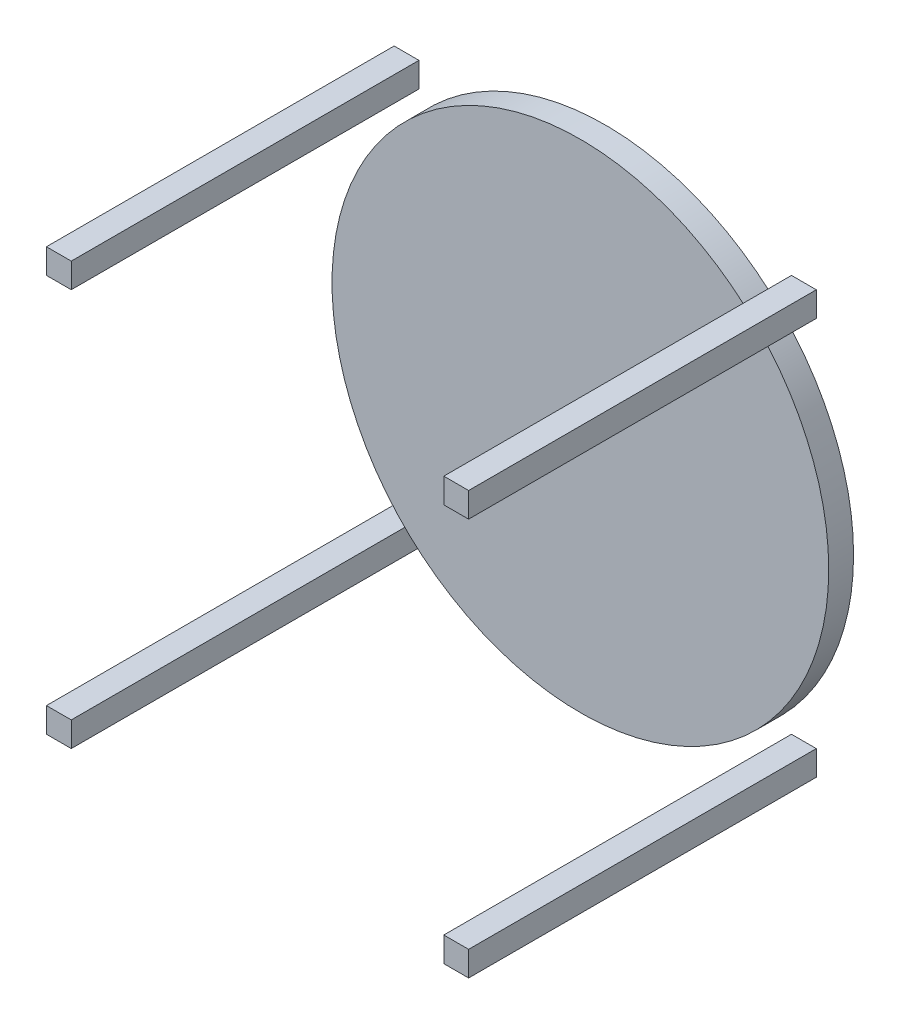
SolidWorks part; units mm, degrees
ref_plane "前视基准面" through (0, 0, 0) normal (0, 0, 1) x (1, 0, 0)
ref_plane "上视基准面" through (0, 0, 0) normal (0, 1, 0) x (1, 0, 0)
ref_plane "右视基准面" through (0, 0, 0) normal (1, 0, 0) x (0, 0, -1)
other "Configuration Table"
sketch "草图1" plane through (0, 0, 0) normal (0, 0, 1) x (1, 0, 0)
  circle A0 centre (0, 0) radius 500
extrude "凸台-拉伸1" add sketch "草图1" along normal blind 50
sketch "草图2" plane through (0, 0, 0) normal (0, 0, 1) x (1, 0, 0)
  line L1 (375, 375) -> (425, 375)
  line L2 (375, 375) -> (375, 425)
  line L3 (375, 425) -> (425, 425)
  line L4 (425, 375) -> (425, 425)
  line L5 (375, 375) -> (425, 425) construction
  line L6 (375, 425) -> (425, 375) construction
  point P0 (400, 400)
extrude "凸台-拉伸2" add sketch "草图2" along normal blind 700
sketch "草图3" plane through (0, 0, 0) normal (0, 0, 1) x (1, 0, 0)
  line L1 (-425, 375) -> (-375, 375)
  line L2 (-425, 375) -> (-425, 425)
  line L3 (-425, 425) -> (-375, 425)
  line L4 (-375, 375) -> (-375, 425)
  line L5 (-425, 375) -> (-375, 425) construction
  line L6 (-425, 425) -> (-375, 375) construction
  point P0 (-400, 400)
extrude "凸台-拉伸3" add sketch "草图3" along normal blind 700
sketch "草图4" plane through (0, 0, 0) normal (0, 0, 1) x (1, 0, 0)
  line L1 (375, -425) -> (425, -425)
  line L2 (375, -425) -> (375, -375)
  line L3 (375, -375) -> (425, -375)
  line L4 (425, -425) -> (425, -375)
  line L5 (375, -425) -> (425, -375) construction
  line L6 (375, -375) -> (425, -425) construction
  point P0 (400, -400)
extrude "凸台-拉伸4" add sketch "草图4" along normal blind 700
sketch "草图5" plane through (0, 0, 0) normal (0, 0, 1) x (1, 0, 0)
  line L1 (-425, -425) -> (-375, -425)
  line L2 (-425, -425) -> (-425, -375)
  line L3 (-425, -375) -> (-375, -375)
  line L4 (-375, -425) -> (-375, -375)
  line L5 (-425, -425) -> (-375, -375) construction
  line L6 (-425, -375) -> (-375, -425) construction
  point P0 (-400, -400)
extrude "凸台-拉伸5" add sketch "草图5" along normal blind 700
sketch "草图6" plane through (0, 0, 0) normal (0, 0, 1) x (1, 0, 0)
  circle A0 centre (0, 0) radius 200
extrude "切除-拉伸1" cut sketch "草图6" along normal blind 20
